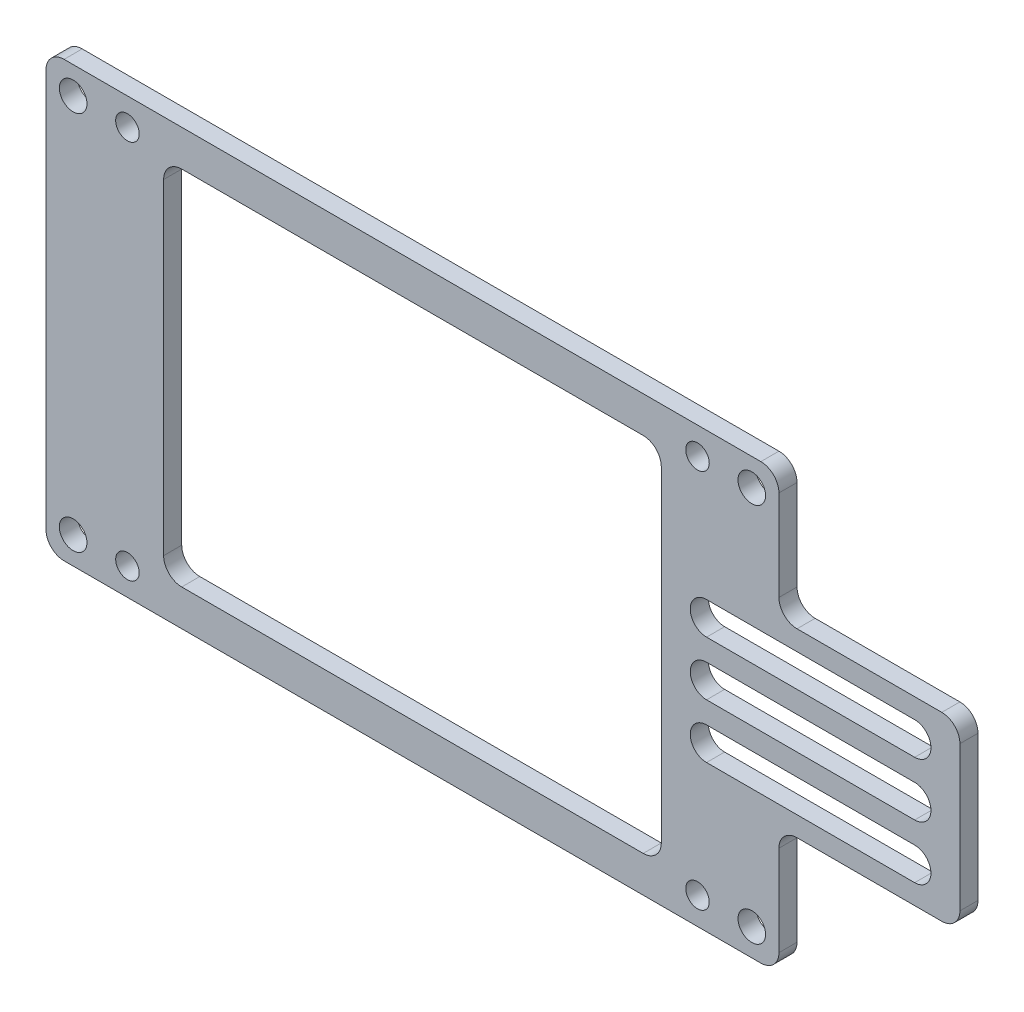
SolidWorks part; units mm, degrees
material "A-玻璃纤维"
ref_plane "前视基准面" through (0, 0, 0) normal (0, 0, 1) x (1, 0, 0)
ref_plane "上视基准面" through (0, 0, 0) normal (0, 1, 0) x (1, 0, 0)
ref_plane "右视基准面" through (0, 0, 0) normal (1, 0, 0) x (0, 0, -1)
other "Configuration Table"
sketch "草图1" plane through (0, 0, 0) normal (0, 0, 1) x (1, 0, 0)
  line L1 (-31.5, -21) -> (31.5, -21) construction
  line L2 (-31.5, -21) -> (-31.5, 21) construction
  line L3 (-31.5, 21) -> (31.5, 21) construction
  line L4 (31.5, -21) -> (31.5, 21) construction
  line L5 (-31.5, -21) -> (31.5, 21) construction
  line L6 (-31.5, 21) -> (31.5, -21) construction
  line L7 (-40.5, -24) -> (40.5, -24)
  line L8 (-40.5, -24) -> (-40.5, 24)
  line L9 (-40.5, 24) -> (40.5, 24)
  line L10 (40.5, -24) -> (40.5, 24)
  line L11 (-40.5, -24) -> (40.5, 24) construction
  line L12 (-40.5, 24) -> (40.5, -24) construction
  circle A0 centre (31.5, -21) radius 1.3
  circle A1 centre (-31.5, -21) radius 1.3
  circle A2 centre (-31.5, 21) radius 1.3
  circle A3 centre (31.5, 21) radius 1.3
  point P0 (0, 0)
  point P10 (0, 0)
  dimension "D3" = 2.6
  dimension "D1" = 63
  dimension "D2" = 42
  dimension "D4" = 48
  dimension "D5" = 81
extrude "凸台-拉伸1" add sketch "草图1" along normal mid plane 2
sketch "草图2" plane through (0, 0, 1) normal (0, 0, 1) x (1, 0, 0)
  line L0 (40.5, -24) -> (40.5, 24) construction
  line L1 (-37.5, -21) -> (37.5, -21) construction
  line L2 (-37.5, -21) -> (-37.5, 21) construction
  line L3 (-37.5, 21) -> (37.5, 21) construction
  line L4 (37.5, -21) -> (37.5, 21) construction
  line L5 (-37.5, -21) -> (37.5, 21) construction
  line L6 (-37.5, 21) -> (37.5, -21) construction
  line L7 (40.5, 24) -> (-40.5, 24) construction
  circle A0 centre (37.5, 21) radius 1.525
  circle A1 centre (37.5, -21) radius 1.525
  circle A2 centre (-37.5, -21) radius 1.525
  circle A3 centre (-37.5, 21) radius 1.525
  point P0 (0, 0)
  dimension "D3" = 3.05
  dimension "D1" = 3
  dimension "D2" = 3
extrude "切除-拉伸1" cut sketch "草图2" against normal mid plane 32
sketch "草图3" plane through (0, 0, 1) normal (0, 0, 1) x (1, 0, 0)
  line L0 (40.5, 24) -> (-40.5, 24) construction
  line L1 (-27.5, -20) -> (27.5, -20)
  line L2 (-27.5, -20) -> (-27.5, 20)
  line L3 (-27.5, 20) -> (27.5, 20)
  line L4 (27.5, -20) -> (27.5, 20)
  line L5 (-27.5, -20) -> (27.5, 20) construction
  line L6 (-27.5, 20) -> (27.5, -20) construction
  circle A0 centre (31.5, 21) radius 1.3 construction
  point P0 (0, 0)
  dimension "D1" = 4
  dimension "D2" = 4
extrude "切除-拉伸2" cut sketch "草图3" against normal mid plane 42
fillet "圆角1" radius 2 8 edges at (-40.5, -24, 0) (-40.5, 24, 0) (40.5, 24, 0) (40.5, -24, 0) (-27.5, 20, 0) (27.5, 20, 0) (27.5, -20, 0) (-27.5, -20, 0)
sketch "草图4" plane through (0, 0, -1) normal (0, 0, -1) x (-1, 0, 0)
  line L0 (-40.5, -22) -> (-40.5, 22) construction
  line L1 (-40.5, -10) -> (-60.5, -10)
  line L2 (-40.5, -10) -> (-40.5, 10)
  line L3 (-40.5, 10) -> (-60.5, 10)
  line L4 (-60.5, -10) -> (-60.5, 10)
  line L5 (-40.5, 0) -> (0, 0) construction
  dimension "D1" = 20
  dimension "D2" = 20
extrude "凸台-拉伸2" add sketch "草图4" against normal blind 2
fillet "圆角2" radius 2 4 edges at (60.5, -10, 0) (40.5, -10, 0) (60.5, 10, 0) (40.5, 10, 0)
sketch "草图5" plane through (0, 0, 1) normal (0, 0, 1) x (1, 0, 0)
  line L0 (60.5, 0) -> (27.5, 0) construction
  line L1 (60.5, 8) -> (60.5, -8) construction
  line L2 (27.5, 18) -> (27.5, -18) construction
  line L3 (32.5, 0) -> (55.5, 0) construction
  line L4 (32.5, 1.8) -> (55.5, 1.8)
  line L5 (32.5, -1.8) -> (55.5, -1.8)
  line L6 (60.5, 3) -> (27.5, 3) construction
  line L7 (32.5, 6) -> (55.5, 6) construction
  line L8 (32.5, 4.2) -> (55.5, 4.2)
  line L9 (32.5, 7.8) -> (55.5, 7.8)
  line L10 (32.5, -6) -> (55.5, -6) construction
  line L11 (32.5, -4.2) -> (55.5, -4.2)
  line L12 (32.5, -7.8) -> (55.5, -7.8)
  arc A0 (32.5, 1.8) -> (32.5, -1.8) centre (32.5, 0) ccw
  arc A1 (55.5, -1.8) -> (55.5, 1.8) centre (55.5, 0) ccw
  arc A2 (32.5, 4.2) -> (32.5, 7.8) centre (32.5, 6) cw
  arc A3 (55.5, 7.8) -> (55.5, 4.2) centre (55.5, 6) cw
  arc A4 (32.5, -4.2) -> (32.5, -7.8) centre (32.5, -6) ccw
  arc A5 (55.5, -7.8) -> (55.5, -4.2) centre (55.5, -6) ccw
  point P9 (44, 0)
  point P19 (44, 6)
  point P26 (44, -6)
  dimension "D1" = 1.8
  dimension "D2" = 23
  dimension "D3" = 3
extrude "切除-拉伸3" cut sketch "草图5" against normal mid plane 22
